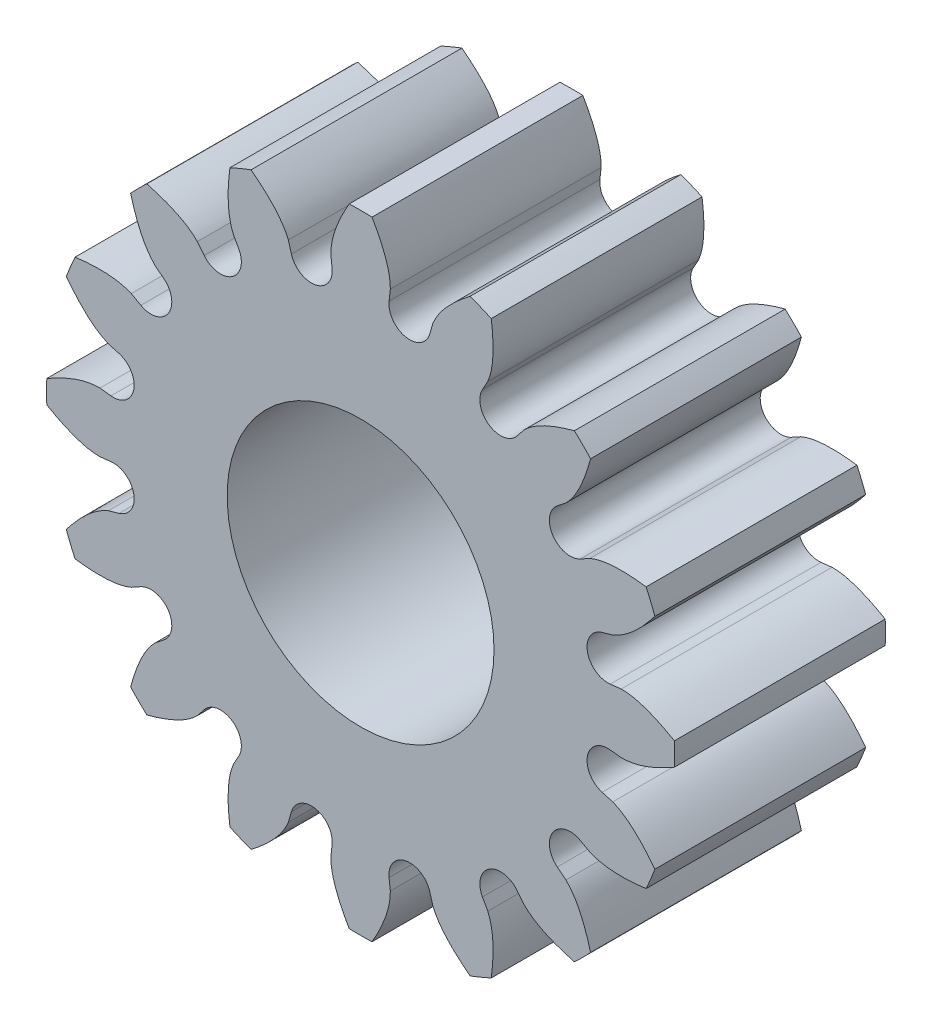
SolidWorks part; units mm, degrees
material "PE Low/Medium Density"
ref_plane "Front Plane" through (0, 0, 0) normal (0, 0, 1) x (1, 0, 0)
ref_plane "Top Plane" through (0, 0, 0) normal (0, 1, 0) x (1, 0, 0)
ref_plane "Right Plane" through (0, 0, 0) normal (1, 0, 0) x (0, 0, -1)
sketch "Involute construction sketch" plane through (0, 0, 0) normal (0, 0, 1) x (1, 0, 0)
  line L0 (0, 0) -> (-1.7884, 3.29) construction
  line L1 (0, 0) -> (-1.0853, 3.5839) construction
  line L2 (0, 0) -> (-0.3374, 3.7294) construction
  line L3 (0, 0) -> (0.4246, 3.7205) construction
  line L4 (-2.9462, 2.3113) -> (-2.4174, 2.8599) construction
  line L5 (-2.4174, 2.8599) -> (-1.7884, 3.29) construction
  line L6 (-1.7884, 3.29) -> (-1.0853, 3.5839) construction
  line L7 (0, 0) -> (-2.4174, 2.8599) construction
  line L8 (0, 0) -> (-2.9462, 2.3113) construction
  line L9 (-1.0853, 3.5839) -> (-0.3374, 3.7294) construction
  line L10 (-0.3374, 3.7294) -> (0.4246, 3.7205) construction
  line L11 (-2.9462, 2.3113) -> (-0.5946, 5.309) construction
  line L12 (-2.4174, 2.8599) -> (-0.0895, 4.8275) construction
  line L13 (-1.7884, 3.29) -> (0.2201, 4.3818) construction
  line L14 (-1.0853, 3.5839) -> (0.3732, 4.0256) construction
  line L15 (-0.3374, 3.7294) -> (0.4215, 3.7981) construction
  line L17 (0, 0) -> (0, 5.7859) construction
  line L18 (0, 0) -> (0.3906, 3.9658) construction
  line L19 (0, 0) -> (0.6442, 3.2386) construction
  circle A0 centre (0, 0) radius 3.302 construction
  circle A1 centre (0, 0) radius 3.7447 construction
  circle A2 centre (0, 0) radius 3.985 construction
  circle A3 centre (0, 0) radius 4.4831 construction
  spline S0 degree 3 poles (0.4246, 3.7205) (0.4261, 3.8242) (0.3767, 4.0544) (0.1137, 4.6484) (-0.2724, 5.0543) (-0.5946, 5.309) knots 0 0 0 0 0.160054 0.360046 1 1 1 1 construction
  point P17 (0.1633, 4.4801)
  dimension "D1" = 6.604
  dimension "D2" = 7.4893
  dimension "D3" = 7.97
  dimension "D4" = 8.9662
  dimension "D5" = 0.762
  dimension "D6" = 1.524
  dimension "D7" = 2.286
  dimension "D8" = 3.048
  dimension "D9" = 3.81
  dimension "D10" = 5.625
  dimension "D11" = 11.25
sketch "Sketch2" plane through (0, 0, 0) normal (0, 0, 1) x (1, 0, 0)
  line L0 (0, 4.4831) -> (0, 3.302)
  line L1 (0, 0) -> (0, 5.7859) construction
  line L2 (0.4246, 3.7205) -> (0.4067, 3.564)
  line L3 (0, 0) -> (0.4246, 3.7205) construction
  circle A0 centre (0, 0) radius 4.4831 construction
  circle A1 centre (0, 0) radius 3.302 construction
  arc A2 (0, 4.4831) -> (0.1633, 4.4801) centre (0, 0) cw
  arc A3 (0, 3.302) -> (0.6442, 3.2386) centre (0, 0) cw
  arc A4 (0.4067, 3.564) -> (0.6442, 3.2386) centre (0.7022, 3.5302) ccw
  spline S0 degree 3 poles (0.4246, 3.7205) (0.4258, 3.8034) (0.3801, 4.0726) (0.2566, 4.3168) (0.1633, 4.4801) knots 0 0 0 0 0.305961 1 1 1 1
sketch "Sketch3" plane through (0, 0, 0) normal (0, 0, 1) x (1, 0, 0)
  circle A0 centre (0, 0) radius 3.302
  circle A1 centre (0, 0) radius 1.905
  dimension "D1" = 6.604
  dimension "D2" = 3.81
extrude "Base" add sketch "Sketch3" along normal blind 3.0099
extrude "Half tooth" add sketch "Sketch2" along normal up to surface (3.0099 mm away) up to face at (3.302, 0, 3.0099)
ref_plane "Midplane of half tooth" through (0, 0, 0) normal (-1, 0, 0) x (0, 0, 1)
mirror "Mirror of half tooth" about plane through (0, 0, 0) normal (-1, 0, 0) of "Half tooth"
pattern_circular "Pattern of tooth" count 16 over 360 of "Half tooth", "Mirror of half tooth"
equation "\"radtodeg\"= 180 / PI'radian to degree conversion [ ]"
equation "\"phi\"= 20'pressure angle [deg]"
equation "\"N\"= 16'number of teeth [teeth]"
equation "\"A\"= 0.353in'diameter of addendum circle [inch]"
equation "\"B\"= 0.260in'diameter of dedendum circle [inch]"
equation "\"P\"= ( \"N\" + 2 ) / \"A\"'diametral pitch [teeth/inch]"
equation "\"d\"= \"N\" / \"P\"'diameter of pitch circle [inch]"
equation "\"cp\"= PI / \"P\"'circular pitch [inch/teeth]"
equation "\"add\"= 1 / \"P\"'addendum [inch]"
equation "\"ded\"= - ( \"B\" - \"d\" ) / 2'dedendum [inch]"
equation "\"clear\"= \"ded\" - \"add\"'clearance [inch]"
equation "\"C\"= \"B\" + 2 * \"clear\"'diameter of clearance circle [inch]"
equation "\"h\"= \"add\" + \"ded\"'tooth height / whole depth [inch]"
equation "\"s\"= \"d\" * cos ( \"phi\" * 1 / \"radtodeg\" )'diameter of base circle [inch]"
equation "\"t\"= ( PI / 2 ) / \"P\"'tooth width at diameter of pitch circle diameter [inch]"
equation "\"alpha\"= ( \"t\" / ( \"d\" / 2 ) * \"radtodeg\" ) / 2'arc angle for half of tooth width at pitch circle diameter [inch]"
equation "\"bore\"= 0.15'bore of hub [inch]"
equation "\"D4@Involute construction sketch\"= \"A\"'addendum circle"
equation "\"D3@Involute construction sketch\"= \"d\"'pitch circle"
equation "\"D2@Involute construction sketch\"= \"s\"'base circle"
equation "\"D1@Involute construction sketch\"= \"B\"'dedendum circle"
equation "\"seg\"= \"D5@Involute construction sketch\"'size of one involute segment [inch]"
equation "\"D6@Involute construction sketch\"=2*\"seg\""
equation "\"D7@Involute construction sketch\"=3*\"seg\""
equation "\"D8@Involute construction sketch\"=4*\"seg\""
equation "\"D9@Involute construction sketch\"=5*\"seg\""
equation "\"D10@Involute construction sketch\"=\"alpha\""
equation "\"D11@Involute construction sketch\"=2*\"alpha\""
equation "\"D1@Sketch3\"=\"B\""
equation "\"D2@Sketch3\"=\"bore\""
